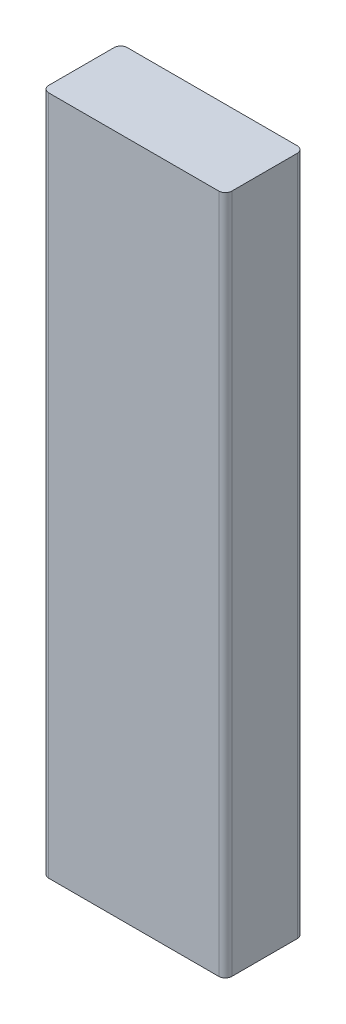
SolidWorks part; units mm, degrees
ref_plane "Front" through (0, 0, 0) normal (0, 0, 1) x (1, 0, 0)
ref_plane "Top" through (0, 0, 0) normal (0, 1, 0) x (1, 0, 0)
ref_plane "Right" through (0, 0, 0) normal (1, 0, 0) x (0, 0, -1)
sketch "Sketch1" plane through (0, 0, 0) normal (0, 1, 0) x (1, 0, 0)
  line L1 (41.275, -19.05) -> (-41.275, -19.05)
  line L2 (44.45, -15.875) -> (44.45, 15.875)
  line L3 (41.275, 19.05) -> (-41.275, 19.05)
  line L4 (-44.45, -15.875) -> (-44.45, 15.875)
  line L5 (44.45, -19.05) -> (-44.45, 19.05) construction
  line L6 (44.45, 19.05) -> (-44.45, -19.05) construction
  arc A0 (-41.275, -19.05) -> (-44.45, -15.875) centre (-41.275, -15.875) cw
  arc A1 (41.275, -19.05) -> (44.45, -15.875) centre (41.275, -15.875) ccw
  arc A2 (44.45, 15.875) -> (41.275, 19.05) centre (41.275, 15.875) ccw
  arc A3 (-41.275, 19.05) -> (-44.45, 15.875) centre (-41.275, 15.875) ccw
  point P0 (0, 0)
  dimension "D1" = 3.175
  dimension "D2" = 38.1
  dimension "D3" = 88.9
extrude "Boss-Extrude1" add sketch "Sketch1" along normal blind 330.2
equation "\"L\" = 13"
equation "\"D1@Boss-Extrude1\"=\"L\""
